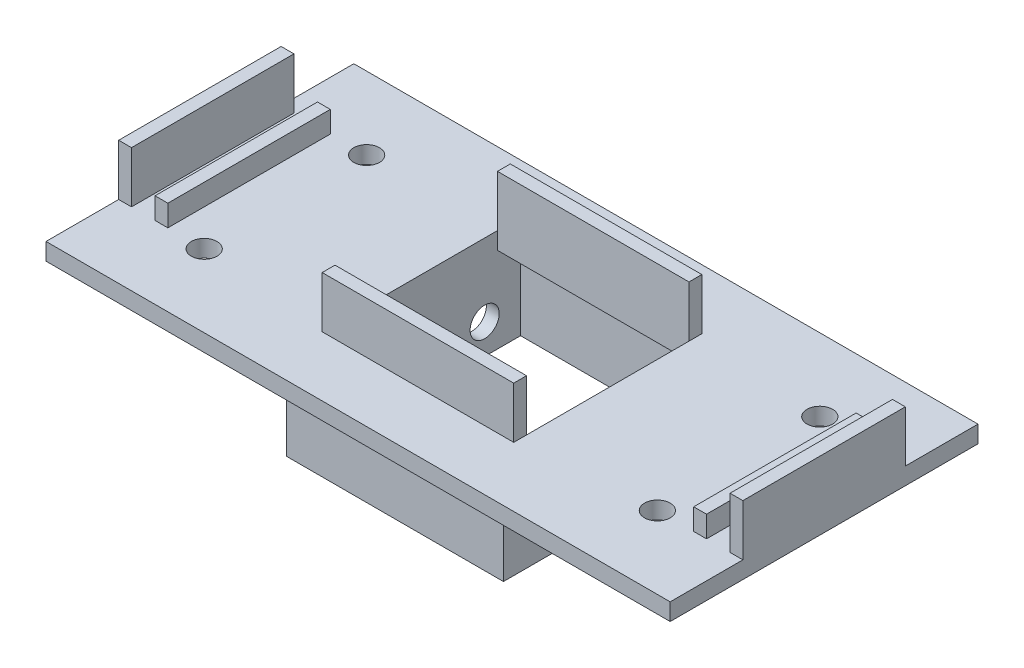
SolidWorks part; units mm, degrees
ref_plane "Front Plane" through (0, 0, 0) normal (0, 0, 1) x (1, 0, 0)
ref_plane "Top Plane" through (0, 0, 0) normal (0, 1, 0) x (1, 0, 0)
ref_plane "Right Plane" through (0, 0, 0) normal (1, 0, 0) x (0, 0, -1)
sketch "Sketch1" plane through (0, 0, 0) normal (0, 1, 0) x (1, 0, 0)
  line L1 (-36.5, 18) -> (36.5, 18)
  line L2 (-36.5, 18) -> (-36.5, -18)
  line L3 (-36.5, -18) -> (36.5, -18)
  line L4 (36.5, 18) -> (36.5, -18)
  line L5 (-36.5, 18) -> (36.5, -18) construction
  line L6 (-36.5, -18) -> (36.5, 18) construction
  point P0 (0, 0)
  dimension "D1" = 36
  dimension "D2" = 73
extrude "Boss-Extrude1" add sketch "Sketch1" along normal blind 2
sketch "Sketch2" plane through (0, 2, 0) normal (0, 1, 0) x (1, 0, 0)
  line L0 (-36.5, 0) -> (36.5, 0) construction
  line L1 (-36.5, 18) -> (-36.5, -18) construction
  line L2 (36.5, -18) -> (36.5, 18) construction
  line L3 (-36.5, 0) -> (-35, 0) construction
  line L4 (-36.5, -9.5) -> (-35, -9.5)
  line L5 (-36.5, -9.5) -> (-36.5, 9.5)
  line L6 (-36.5, 9.5) -> (-35, 9.5)
  line L7 (-35, -9.5) -> (-35, 9.5)
  line L8 (36.5, 9.5) -> (35, 9.5)
  line L9 (36.5, 9.5) -> (36.5, -9.5)
  line L10 (36.5, -9.5) -> (35, -9.5)
  line L11 (35, 9.5) -> (35, -9.5)
  line L12 (35, 0) -> (36.5, 0) construction
  dimension "D1" = 19
  dimension "D2" = 1.5
  dimension "D3" = 1.5
extrude "Boss-Extrude2" add sketch "Sketch2" along normal blind 6
sketch "Sketch3" plane through (0, 0, 0) normal (0, -1, 0) x (1, 0, 0)
  line L0 (-11.2, 12.2) -> (11.2, 12.2)
  line L1 (-12.7, 13.7) -> (12.7, 13.7)
  line L2 (-12.7, 13.7) -> (-12.7, -13.7)
  line L3 (-12.7, -13.7) -> (12.7, -13.7)
  line L4 (12.7, 13.7) -> (12.7, -13.7)
  line L5 (-12.7, 13.7) -> (12.7, -13.7) construction
  line L6 (-12.7, -13.7) -> (12.7, 13.7) construction
  line L7 (11.2, 12.2) -> (11.2, -12.2)
  line L8 (-11.2, -12.2) -> (11.2, -12.2)
  line L9 (-11.2, 12.2) -> (-11.2, -12.2)
  point P0 (0, 0)
  dimension "D1" = 25.4
  dimension "D2" = 27.4
  dimension "D3" = 1.5
extrude "Boss-Extrude3" add sketch "Sketch3" along normal blind 10
sketch "Sketch4" plane through (0, 0, 0) normal (0, -1, 0) x (1, 0, 0)
  line L1 (-11.2, 9.5) -> (11.2, 9.5)
  line L2 (-11.2, 9.5) -> (-11.2, -9.5)
  line L3 (-11.2, -9.5) -> (11.2, -9.5)
  line L4 (11.2, 12.2) -> (-11.2, 12.2)
  line L5 (-11.2, 12.2) -> (-11.2, -12.2)
  line L6 (-11.2, -12.2) -> (11.2, -12.2)
  line L7 (11.2, -12.2) -> (11.2, 12.2)
  line L8 (11.2, 12.2) -> (-11.2, 12.2)
  line L9 (-11.2, 12.2) -> (-11.2, -12.2)
  line L10 (-11.2, -12.2) -> (11.2, -12.2)
  line L11 (11.2, -12.2) -> (11.2, 12.2)
  line L12 (11.2, 9.5) -> (11.2, -9.5)
  line L13 (-11.2, 9.5) -> (11.2, -9.5) construction
  line L14 (-11.2, -9.5) -> (11.2, 9.5) construction
  point P2 (0, 0)
  line M6 (-11.2, 12.2) -> (-11.2, -12.2)
  line M8 (11.2, -12.2) -> (11.2, 12.2)
  dimension "D2" = 19
  dimension "D1" = 0
extrude "Cut-Extrude1" cut sketch "Sketch4" against normal through all contours L3 L1 M6 M8
sketch "Sketch5" plane through (0, 2, 0) normal (0, 1, 0) x (1, 0, 0)
  line L0 (11.2, -9.5) -> (11.2, 9.5) construction
  line L1 (-11.2, 9.5) -> (11.2, 9.5)
  line L2 (-11.2, 9.5) -> (-11.2, 11)
  line L3 (-11.2, 11) -> (11.2, 11)
  line L4 (11.2, 9.5) -> (11.2, 11)
  line L5 (-11.2, -9.5) -> (11.2, -9.5)
  line L6 (-11.2, -9.5) -> (-11.2, -11)
  line L7 (-11.2, -11) -> (11.2, -11)
  line L8 (11.2, -9.5) -> (11.2, -11)
  line L9 (-11.2, 9.5) -> (-11.2, -9.5) construction
  dimension "D1" = 1.5
  dimension "D2" = 1.5
extrude "Boss-Extrude4" add sketch "Sketch5" along normal blind 6
sketch "Sketch6" plane through (0, 2, 0) normal (0, 1, 0) x (1, 0, 0)
  line L0 (-36.5, 9.5) -> (36.5, 9.5) construction
  line L1 (-36.5, 18) -> (-36.5, 9.5) construction
  line L2 (36.5, 9.5) -> (36.5, 18) construction
  line L3 (-36.5, -9.5) -> (36.5, -9.5) construction
  line L4 (-36.5, -9.5) -> (-36.5, -18) construction
  line L5 (36.5, -18) -> (36.5, -9.5) construction
  line L6 (-11.2, 9.5) -> (11.2, 9.5) construction
  line L7 (11.2, -9.5) -> (-11.2, -9.5) construction
  line L8 (-26.5, 9.5) -> (-26.5, -9.5) construction
  line L9 (26.5, 9.5) -> (26.5, -9.5) construction
  line L10 (-36.5, 9.5) -> (-36.5, -9.5) construction
  line L11 (36.5, -9.5) -> (36.5, 9.5) construction
  circle A0 centre (-26.5, 9.5) radius 1.5
  circle A1 centre (-26.5, -9.5) radius 1.5
  circle A2 centre (26.5, 9.5) radius 1.5
  circle A3 centre (26.5, -9.5) radius 1.5
  dimension "D3" = 3
  dimension "D1" = 10
  dimension "D2" = 10
extrude "Cut-Extrude2" cut sketch "Sketch6" against normal through all
sketch "Sketch7" plane through (0, 2, 0) normal (0, 1, 0) x (1, 0, 0)
  line L0 (-36.5, 0) -> (36.5, 0) construction
  line L2 (-36.5, 9.5) -> (-36.5, -9.5) construction
  line L3 (36.5, -9.5) -> (36.5, 9.5) construction
  line L7 (-32.25, 9.5) -> (-30.75, 9.5)
  line L8 (-26.5, 9.5) -> (-26.5, -9.5) construction
  line L9 (26.5, 9.5) -> (26.5, -9.5) construction
  line L10 (-32.25, 9.5) -> (-32.25, -9.5)
  line L11 (-32.25, -9.5) -> (-30.75, -9.5)
  line L12 (-30.75, 9.5) -> (-30.75, -9.5)
  line L13 (-32.25, 9.5) -> (-30.75, -9.5) construction
  line L14 (-32.25, -9.5) -> (-30.75, 9.5) construction
  line L15 (30.75, 9.5) -> (32.25, 9.5)
  line L16 (30.75, 9.5) -> (30.75, -9.5)
  line L17 (30.75, -9.5) -> (32.25, -9.5)
  line L18 (32.25, 9.5) -> (32.25, -9.5)
  line L19 (30.75, 9.5) -> (32.25, -9.5) construction
  line L20 (30.75, -9.5) -> (32.25, 9.5) construction
  line L21 (-35, -9.5) -> (-35, 9.5) construction
  point P2 (-31.5, 0)
  point P11 (31.5, 0)
  dimension "D1" = 1.5
  dimension "D2" = 1.5
  dimension "D3" = 5
  dimension "D4" = 5
extrude "Boss-Extrude5" add sketch "Sketch7" along normal blind 2.5
sketch "Sketch8" plane through (12.7, 0, 0) normal (1, 0, 0) x (0, 0, -1)
  line L0 (0, 0) -> (0, -10) construction
  line L1 (13.7, -10) -> (-13.7, -10) construction
  line L2 (-8, 0) -> (-8, -10) construction
  line L3 (-18, 0) -> (18, 0) construction
  line L4 (8, 0) -> (8, -10) construction
  line L5 (13.7, 0) -> (-13.7, 0) construction
  circle A0 centre (-8, -6.5) radius 1.7
  circle A1 centre (8, -6.5) radius 1.7
  dimension "D3" = 3.4
  dimension "D4" = 3.4
  dimension "D1" = 8
  dimension "D2" = 8
  dimension "D5" = 6.5
  dimension "D6" = 6.5
extrude "Cut-Extrude3" cut sketch "Sketch8" against normal through all
